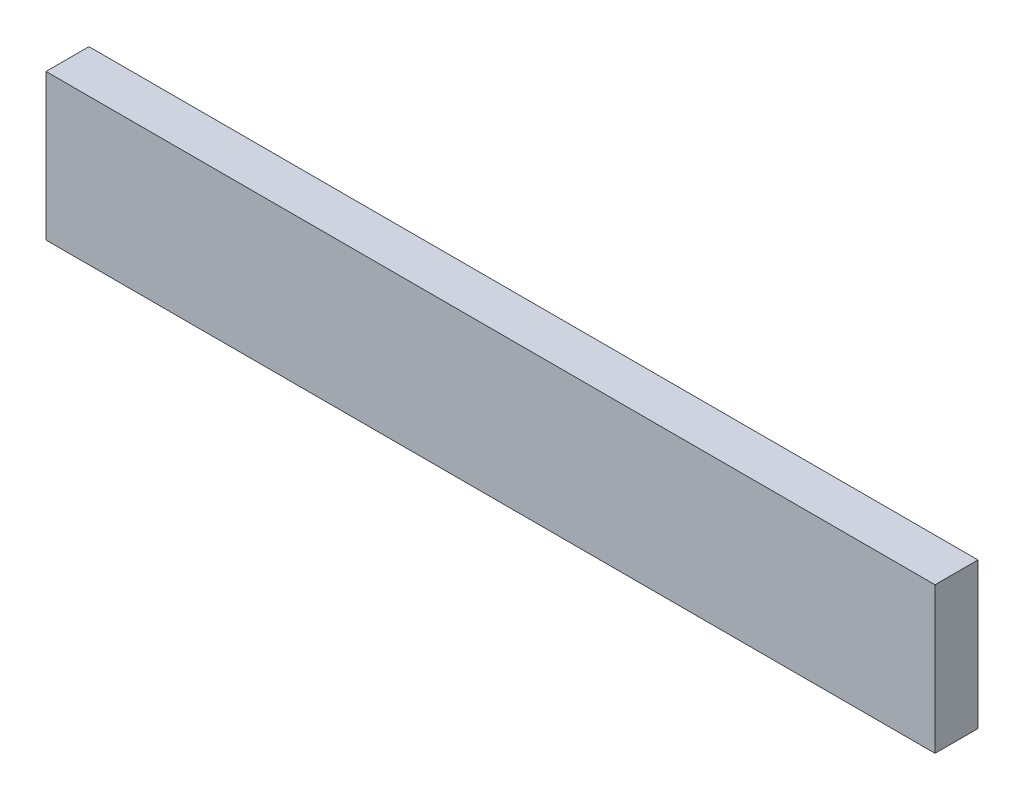
SolidWorks part; units mm, degrees
material "Teak"
ref_plane "Ebene vorne" through (0, 0, 0) normal (0, 0, 1) x (1, 0, 0)
ref_plane "Ebene oben" through (0, 0, 0) normal (0, 1, 0) x (1, 0, 0)
ref_plane "Ebene rechts" through (0, 0, 0) normal (1, 0, 0) x (0, 0, -1)
sketch "Skizze1" plane through (0, 0, 0) normal (0, 0, 1) x (1, 0, 0)
  line L1 (-103.5, -17) -> (103.5, -17)
  line L2 (-103.5, -17) -> (-103.5, 17)
  line L3 (-103.5, 17) -> (103.5, 17)
  line L4 (103.5, -17) -> (103.5, 17)
  line L5 (-103.5, -17) -> (103.5, 17) construction
  line L6 (-103.5, 17) -> (103.5, -17) construction
  point P0 (0, 0)
  dimension "D1" = 207
  dimension "D2" = 34
extrude "Aufsatz-Linear austragen1" add sketch "Skizze1" along normal blind 10
